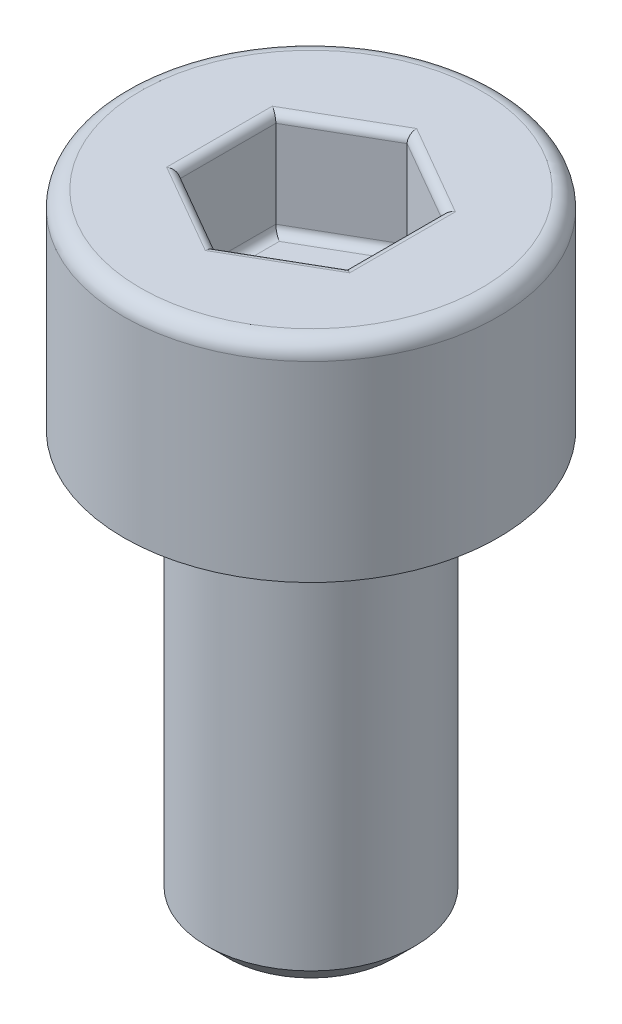
SolidWorks part; units mm, degrees
ref_plane "Front Plane" through (0, 0, 0) normal (0, 0, 1) x (1, 0, 0)
ref_plane "Top Plane" through (0, 0, 0) normal (0, 1, 0) x (1, 0, 0)
ref_plane "Right Plane" through (0, 0, 0) normal (1, 0, 0) x (0, 0, -1)
sketch "Sketch1" plane through (0, 0, 0) normal (0, 0, 1) x (1, 0, 0)
  line L0 (0, 0) -> (0, -47.0967) construction
  line L1 (0, -7.5) -> (-1.25, -7.5)
  line L2 (-1.25, -7.5) -> (-1.25, -2.5)
  line L3 (-1.25, -2.5) -> (-2.25, -2.5)
  line L4 (-2.25, -2.5) -> (-2.25, 0)
  line L5 (-2.25, 0) -> (0, 0)
  line L6 (0, 0) -> (0, -7.5)
  dimension "D1" = 5
  dimension "d" = 2.5
  dimension "k" = 2.5
  dimension "dk" = 4.5
revolve "Revolve1" add sketch "Sketch1" angle 360 about L0
chamfer "Chamfer1" distance 0.25 angle 45 2 edges at (0, -2.5, 1.25) (0, -7.5, 1.25)
fillet "Fillet1" radius 0.2 1 edges at (0, 0, 2.25)
sketch "Sketch2" plane through (0, 0, 0) normal (0, 1, 0) x (1, 0, 0)
  line L1 (0, 1.1547) -> (-1, 0.5774)
  line L2 (-1, 0.5774) -> (-1, -0.5774)
  line L3 (-1, -0.5774) -> (0, -1.1547)
  line L4 (0, -1.1547) -> (1, -0.5774)
  line L5 (1, -0.5774) -> (1, 0.5774)
  line L6 (1, 0.5774) -> (0, 1.1547)
  circle A0 centre (0, 0) radius 1 construction
  dimension "s" = 2
extrude "Cut-Extrude1" cut sketch "Sketch2" against normal blind 1.25
fillet "Fillet2" radius 0.1 12 edges at (-0.5, 0, -0.866) (-1, 0, 0) (-0.5, 0, 0.866) (0.5, 0, 0.866) (1, 0, 0) (0.5, 0, -0.866) (1, -1.25, 0) (0.5, -1.25, 0.866) (-0.5, -1.25, 0.866) (-1, -1.25, 0) (-0.5, -1.25, -0.866) (0.5, -1.25, -0.866)
